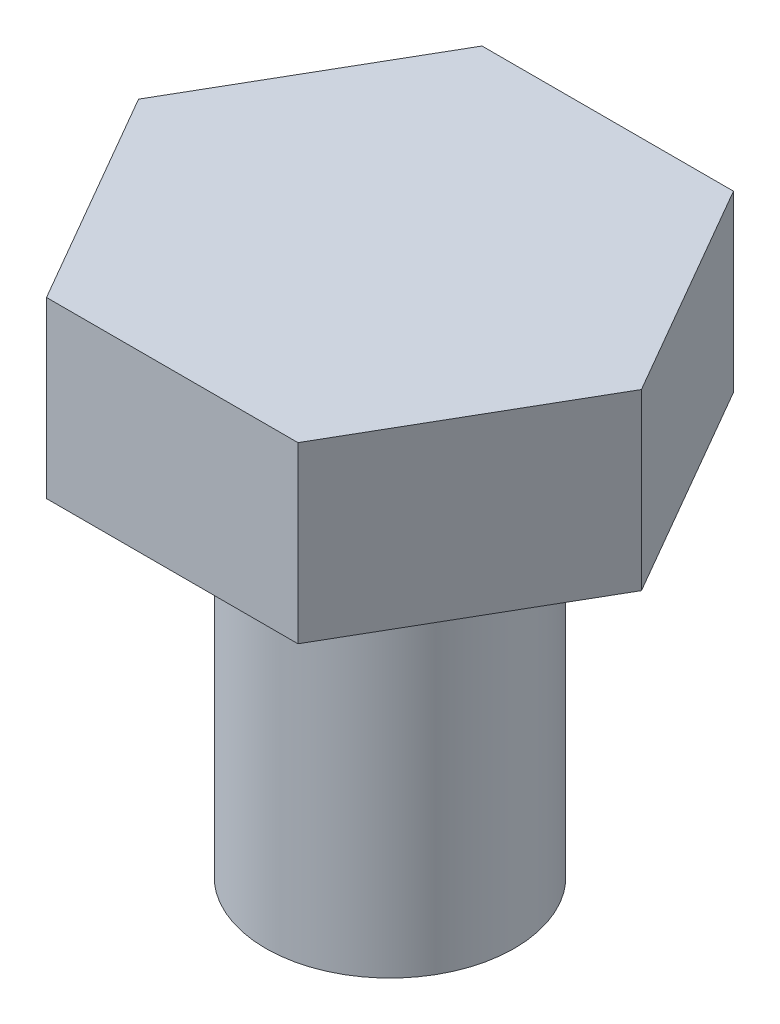
SolidWorks part; units mm, degrees
material "Acier allié"
ref_plane "Face" through (0, 0, 0) normal (0, 0, 1) x (1, 0, 0)
ref_plane "Dessus" through (0, 0, 0) normal (0, 1, 0) x (1, 0, 0)
ref_plane "Droite" through (0, 0, 0) normal (1, 0, 0) x (0, 0, -1)
sketch "Esquisse1" plane through (0, 0, 0) normal (0, 1, 0) x (1, 0, 0)
  circle A0 centre (0, 0) radius 2
  dimension "D1" = 4
extrude "Boss.-Extru.1" add sketch "Esquisse1" against normal blind 6
sketch "Esquisse2" plane through (0, 0, 0) normal (0, 1, 0) x (1, 0, 0)
  line L1 (-4.0415, 0) -> (-2.0207, -3.5)
  line L2 (-2.0207, -3.5) -> (2.0207, -3.5)
  line L3 (2.0207, -3.5) -> (4.0415, 0)
  line L4 (4.0415, 0) -> (2.0207, 3.5)
  line L5 (2.0207, 3.5) -> (-2.0207, 3.5)
  line L6 (-2.0207, 3.5) -> (-4.0415, 0)
  circle A0 centre (0, 0) radius 3.5 construction
  dimension "D1" = 7
extrude "Boss.-Extru.2" add sketch "Esquisse2" along normal blind 2.8
sketch "Esquisse3" plane through (0, 0, 0) normal (1, 0, 0) x (0, 0, -1)
  line L0 (-3.5, -0.01) -> (3.5, -0.01)
  line L1 (-3.5, 2.8) -> (-3.5, 0) construction
  line L2 (3.5, 2.8) -> (3.5, 0) construction
  line L3 (-2, -6) -> (2, -6) construction
  dimension "D1" = 5.99
split line "Ligne de séparation1"
cosmetic thread "Représentation de filetage1" parameters "D2"=3.14
equation "\"d\"=4"
equation "\"D1@Esquisse1\"=\"d\""
equation "\"L\"=6"
equation "\"D1@Boss.-Extru.1\"=\"L\""
equation "\"W\"=7"
equation "\"D1@Esquisse2\"=\"W\""
equation "\"H\"=2.8"
equation "\"D1@Boss.-Extru.2\"=\"H\""
equation "\"Lt\"=5.99"
equation "\"D1@Esquisse3\"=\"Lt\""
equation "\"dr\"=3.14"
equation "\"D2@Représentation de filetage1\"=\"dr\""
